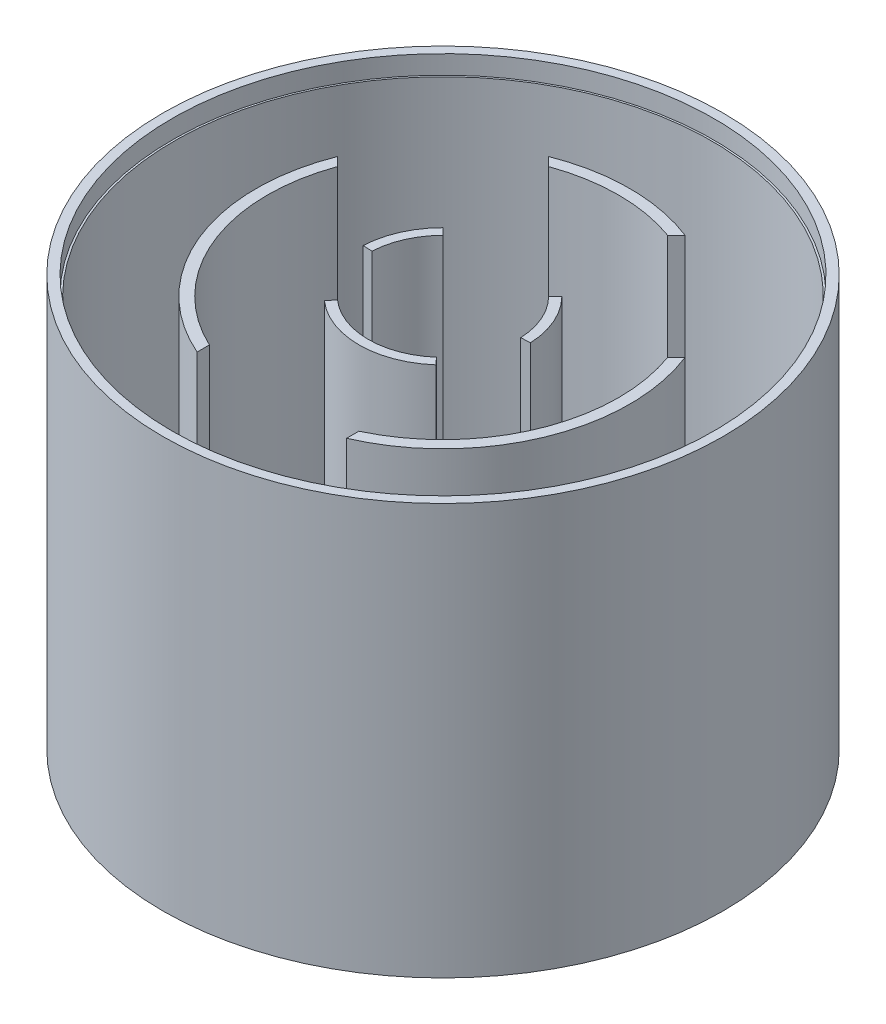
SolidWorks part; units mm, degrees
ref_plane "Front Plane" through (0, 0, 0) normal (0, 0, 1) x (1, 0, 0)
ref_plane "Top Plane" through (0, 0, 0) normal (0, 1, 0) x (1, 0, 0)
ref_plane "Right Plane" through (0, 0, 0) normal (1, 0, 0) x (0, 0, -1)
sketch "Sketch1" plane through (0, 0, 0) normal (0, 1, 0) x (1, 0, 0)
  circle A0 centre (0, 0) radius 75
  dimension "D1" = 150
extrude "Boss-Extrude1" add sketch "Sketch1" along normal blind 110
sketch "Sketch2" plane through (0, 110, 0) normal (0, 1, 0) x (1, 0, 0)
  circle A0 centre (0, 0) radius 72
  dimension "D1" = 144
extrude "Cut-Extrude1" cut sketch "Sketch2" against normal blind 100
sketch "Sketch3" plane through (0, 110, 0) normal (0, 1, 0) x (1, 0, 0)
  circle A0 centre (0, 0) radius 72.5
  dimension "D1" = 145
extrude "Cut-Extrude2" cut sketch "Sketch3" against normal blind 5
sketch "Sketch8" plane through (0, 10, 0) normal (0, 1, 0) x (1, 0, 0)
  circle A0 centre (0, 0) radius 50
  circle A1 centre (0, 0) radius 47
  dimension "D1" = 100
  dimension "D2" = 94
extrude "Boss-Extrude4" add sketch "Sketch8" along normal blind 95
sketch "Sketch10" plane through (0, 10, 0) normal (0, 1, 0) x (1, 0, 0)
  circle A0 centre (0, 0) radius 20
  circle A1 centre (0, 0) radius 22.5
  dimension "D1" = 40
  dimension "D2" = 45
extrude "Boss-Extrude5" add sketch "Sketch10" along normal blind 95
sketch "Sketch11" plane through (0, 105, 0) normal (0, 1, 0) x (1, 0, 0)
  line L0 (0, 0) -> (-29.7143, 1.4359)
  line L1 (-29.7143, 1.4359) -> (-20, -22.6)
  line L2 (-20, -22.6) -> (0, 0)
  line L3 (0, 0) -> (-35.3524, 35.3583) construction
  line L4 (0, 0) -> (35.3583, 35.3524)
  line L5 (0, 0) -> (0, -50)
  line L6 (-35.3524, 35.3583) -> (-49.4945, 21.2161)
  line L7 (-49.4945, 21.2161) -> (-29.7143, 1.4359)
  line L8 (-35.3524, 35.3583) -> (-21.2103, 49.5004)
  line L9 (-21.2103, 49.5004) -> (-2.2548, 30.545)
  line L10 (0, -50) -> (-20, -50)
  line L11 (-20, -50) -> (0, -50)
  line L12 (0, -50) -> (20, -50)
  line L13 (-20, -50) -> (-20, -22.6)
  line L14 (20, -50) -> (20, -22.6)
  line L15 (35.3583, 35.3524) -> (21.2173, 49.4957)
  line L16 (21.2173, 49.4957) -> (2.486, 30.7675)
  line L17 (35.3583, 35.3524) -> (49.4992, 21.2091)
  line L18 (49.4992, 21.2091) -> (29.5095, 1.2226)
  line L19 (-29.7143, 1.4359) -> (-2.2548, 30.545)
  line L20 (2.486, 30.7675) -> (29.5095, 1.2226)
  line L21 (-20, -22.6) -> (20, -22.6)
  line L25 (0, 0) -> (20, -22.6)
  line L26 (29.5095, 1.2226) -> (20, -22.6)
  line L27 (0, 0) -> (29.5095, 1.2226)
  line L29 (-15.9846, 15.9904) -> (-2.2548, 30.545)
  line L30 (2.486, 30.7675) -> (-2.2548, 30.545)
  line L31 (2.486, 30.7675) -> (15.9978, 15.9951)
  line L32 (15.9978, 15.9951) -> (0, 0)
  circle A0 centre (0, 0) radius 50 construction
  circle A2 centre (0, 0) radius 22.5 construction
  circle M12 centre (0, 0) radius 22.5
  circle M13 centre (0, 0) radius 20
  dimension "D1" = 20
  dimension "D2" = 20
  dimension "D3" = 20
  dimension "D4" = 20
  dimension "D5" = 20
  dimension "D6" = 20
  dimension "D7" = 22.6
  dimension "D8" = 22.6
  dimension "D9" = 22.6
  dimension "D10" = 50
extrude "Cut-Extrude3" cut sketch "Sketch11" against normal blind 95 contours L21 L13 L10 L5 | L21 L5 L12 L14 | L3 L19 L9 L8 | L19 L3 L6 L7 | L16 L20 L4 L15 | L4 L20 L18 L17 | L2 L0 M12 M13 | L27 L25 M13 M12 | L3 L4 M13 M12
